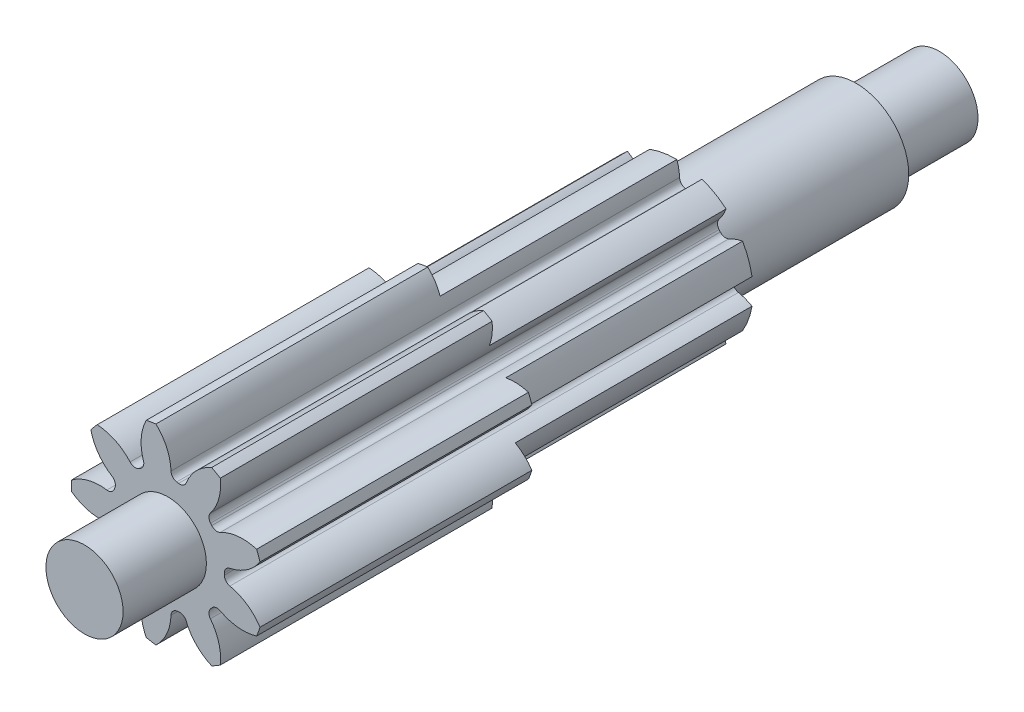
SolidWorks part; units mm, degrees
ref_plane "Front Plane" through (0, 0, 0) normal (0, 0, 1) x (1, 0, 0)
ref_plane "Top Plane" through (0, 0, 0) normal (0, 1, 0) x (1, 0, 0)
ref_plane "Right Plane" through (0, 0, 0) normal (1, 0, 0) x (0, 0, -1)
sketch "Sketch1" plane through (0, 0, 0) normal (0, 0, 1) x (1, 0, 0)
  line L0 (0, 0) -> (0, 0.9) construction
  line L1 (-0.2893, 1.0053) -> (0.2893, 0.7947) construction
  circle A0 centre (0, 0) radius 0.65 construction
  circle A1 centre (0, 0) radius 1.1 construction
  circle A2 centre (0, 0) radius 0.9 construction
  circle A3 centre (0, 0) radius 0.8457 construction
  circle A5 centre (0, 0) radius 0.5 construction
  point P8 (0.1, 0)
  point P13 (4.5, 0)
  dimension "OD" = 2.2
  dimension "Root Diameter" = 1.3
  dimension "Gear Pitch Diameter" = 1.8
  dimension "Base Diameter" = 1.6914
  dimension "For Shaft Diameter" = 1
  dimension "Pressure Angle" = 20
  dimension "Number of Teeth" = 9
  dimension "Module" = 0.2
sketch "Sketch2" plane through (0, 0, 0) normal (1, 0, 0) x (0, 0, -1)
  line L0 (-4.875, 0) -> (4.875, 0) construction
  line L1 (4.875, 1.1) -> (4.875, -1.1) construction
  line L3 (-4.875, 1.1) -> (4.875, 1.1) construction
  line L5 (-4.875, 12.5) -> (-4.875, -12.5) construction
  point P2 (0, 1.1)
  dimension "Overall Width" = 9.75
  dimension "Face Width" = 4.875
sketch "Sketch3" plane through (0, 0, 0) normal (0, 0, 1) x (1, 0, 0)
  circle A0 centre (0, 0) radius 1.1
  circle A1 centre (0, 0) radius 1.1 construction
extrude "Boss-Extrude1" add sketch "Sketch3" against normal up to vertex (4.875 mm away) and the other way up to vertex (4.875 mm away) up to point (0, 0, -4.875) other way up to point (0, 0, 4.875)
sketch "Sketch4" plane through (0, 0, 0) normal (0, 0, 1) x (1, 0, 0)
  line L0 (0.6452, -0.0785) -> (0.6452, 0.0785)
  arc A3 (1.0517, 0.3225) -> (1.0517, -0.3225) centre (0, 0) cw
  circle A4 centre (0, 0) radius 1.1 construction
  arc A5 (1.0517, 0.3225) -> (0.6452, 0.0785) centre (0.5964, 0.6204) cw
  circle A6 centre (0, 0) radius 0.65 construction
  arc A7 (1.0517, -0.3225) -> (0.6452, -0.0785) centre (0.5964, -0.6204) ccw
  spline S0 degree 4 poles (0.835, 0.1344) (0.8354, 0.1345) (0.8366, 0.1347) (0.8388, 0.1353) (0.8424, 0.1363) (0.847, 0.1378) (0.8528, 0.1399) (0.8596, 0.1427) (0.8669, 0.146) (0.8748, 0.1499) (0.8826, 0.1541) (0.8902, 0.1585) (0.8977, 0.1631) (0.9066, 0.1689) (0.9172, 0.1763) (0.9293, 0.1854) (0.9427, 0.1963) (0.9559, 0.208) (0.9686, 0.22) (0.9811, 0.2327) (0.9929, 0.2454) (1.0047, 0.2591) (1.0154, 0.2721) (1.0269, 0.287) (1.0362, 0.2996) (1.05, 0.3198) (1.0557, 0.3287) (1.0642, 0.3422) (1.067, 0.347) knots 0 0 0 0 0 0.005377 0.015084 0.028532 0.04661 0.064855 0.092111 0.119476 0.146842 0.174209 0.201575 0.228941 0.256307 0.307035 0.361767 0.4165 0.471232 0.525964 0.580697 0.635429 0.690161 0.744894 0.799626 0.854358 0.909091 1 1 1 1 1 construction
  spline S1 degree 4 poles (0.835, 0.1344) (0.8354, 0.1345) (0.8366, 0.1347) (0.8388, 0.1353) (0.8424, 0.1363) (0.847, 0.1378) (0.8528, 0.1399) (0.8596, 0.1427) (0.8669, 0.146) (0.8748, 0.1499) (0.8826, 0.1541) (0.8902, 0.1585) (0.8977, 0.1631) (0.9066, 0.1689) (0.9172, 0.1763) (0.9293, 0.1854) (0.9427, 0.1963) (0.9559, 0.208) (0.9686, 0.22) (0.9811, 0.2327) (0.9929, 0.2454) (1.0047, 0.2591) (1.0154, 0.2721) (1.0269, 0.287) (1.0362, 0.2996) (1.0451, 0.3126) (1.0495, 0.3192) (1.0517, 0.3225) knots 0 0 0 0 0 0.005377 0.015084 0.028532 0.04661 0.064855 0.092111 0.119476 0.146842 0.174209 0.201575 0.228941 0.256307 0.307035 0.361767 0.4165 0.471232 0.525964 0.580697 0.635429 0.690161 0.744894 0.799626 0.854358 0.909091 0.909091 0.909091 0.909091 0.909091 construction
  spline S2 degree 4 poles (0.835, -0.1344) (0.8354, -0.1345) (0.8366, -0.1347) (0.8388, -0.1353) (0.8424, -0.1363) (0.847, -0.1378) (0.8528, -0.1399) (0.8596, -0.1427) (0.8669, -0.146) (0.8748, -0.1499) (0.8826, -0.1541) (0.8902, -0.1585) (0.8977, -0.1631) (0.9066, -0.1689) (0.9172, -0.1763) (0.9293, -0.1854) (0.9427, -0.1963) (0.9559, -0.208) (0.9686, -0.22) (0.9811, -0.2327) (0.9929, -0.2454) (1.0047, -0.2591) (1.0154, -0.2721) (1.0269, -0.287) (1.0362, -0.2996) (1.05, -0.3198) (1.0557, -0.3287) (1.0642, -0.3422) (1.067, -0.347) knots 0 0 0 0 0 0.005377 0.015084 0.028532 0.04661 0.064855 0.092111 0.119476 0.146842 0.174209 0.201575 0.228941 0.256307 0.307035 0.361767 0.4165 0.471232 0.525964 0.580697 0.635429 0.690161 0.744894 0.799626 0.854358 0.909091 1 1 1 1 1 construction
  spline S3 degree 4 poles (0.835, -0.1344) (0.8354, -0.1345) (0.8366, -0.1347) (0.8388, -0.1353) (0.8424, -0.1363) (0.847, -0.1378) (0.8528, -0.1399) (0.8596, -0.1427) (0.8669, -0.146) (0.8748, -0.1499) (0.8826, -0.1541) (0.8902, -0.1585) (0.8977, -0.1631) (0.9066, -0.1689) (0.9172, -0.1763) (0.9293, -0.1854) (0.9427, -0.1963) (0.9559, -0.208) (0.9686, -0.22) (0.9811, -0.2327) (0.9929, -0.2454) (1.0047, -0.2591) (1.0154, -0.2721) (1.0269, -0.287) (1.0362, -0.2996) (1.0451, -0.3126) (1.0495, -0.3192) (1.0517, -0.3225) knots 0 0 0 0 0 0.005377 0.015084 0.028532 0.04661 0.064855 0.092111 0.119476 0.146842 0.174209 0.201575 0.228941 0.256307 0.307035 0.361767 0.4165 0.471232 0.525964 0.580697 0.635429 0.690161 0.744894 0.799626 0.854358 0.909091 0.909091 0.909091 0.909091 0.909091 construction
  dimension "D1" = 0.1571
extrude "Cut-Extrude1" cut sketch "Sketch4" against normal through all both and the other way through all
fillet "Fillet1" radius 0.0785 2 edges at (0.6452, -0.0785, 0) (0.6452, 0.0785, 0)
pattern_circular "CirPattern1" count 9 over 360 about axis through (0, 0, 0) along (0, 0, 1) of "Cut-Extrude1", "Fillet1"
sketch "Sketch5" plane through (0, 0, 0) normal (1, 0, 0) x (0, 0, -1)
  line L0 (-5.9186, 0) -> (3.9532, 0) construction
  line L9 (4.875, 0) -> (-4.875, 0) construction
  line L10 (4.875, 1.3) -> (4.875, 0.44)
  line L11 (4.875, 0.44) -> (3.925, 0.44)
  line L12 (3.925, 0.44) -> (3.925, 0.6)
  line L13 (1.875, 0.875) -> (-0.825, 0.875)
  line L14 (-0.825, 0.875) -> (-0.825, 1.3)
  line L15 (-0.825, 1.3) -> (4.875, 1.3)
  line L16 (4.875, -0.0566) -> (4.875, 0.0566) construction
  line L17 (1.875, 0.875) -> (1.875, 0.6)
  line L18 (1.875, 0.6) -> (3.925, 0.6)
  line L19 (-4.875, 0.1651) -> (-4.875, 0.0566) construction
  line L20 (-4.875, 1.3) -> (-3.925, 1.3)
  line L21 (-4.875, 1.3) -> (-4.875, 0.44)
  line L22 (-4.875, 0.44) -> (-3.925, 0.44)
  line L23 (-3.925, 1.3) -> (-3.925, 0.44)
  dimension "D1" = 0.88
  dimension "D2" = 1.75
  dimension "D3" = 2.6
  dimension "D4" = 0.95
  dimension "D5" = 1.2
  dimension "D6" = 2.7
  dimension "D7" = 3
  dimension "D8" = 0.95
revolve "Cut-Revolve1" cut sketch "Sketch5" angle 360 about L0
equation "\"Number of Teeth\"= 9"
equation "\"Module\"= 0.2"
equation "\"Diametral Pitch\"= 1 / \"Module\""
equation "\"Dedendum\"= 1.25 / \"Diametral Pitch\""
equation "\"Pitch Diameter\"= \"Module\" * \"Number of Teeth\""
equation "\"Root Diameter\"= \"Pitch Diameter\" - ( 2 * \"Dedendum\" )"
equation "\"Root Diameter@Sketch1\"=\"Root Diameter\""
equation "\"OD@Sketch1\" = \"Outside Diameter\""
equation "\"D1@CirPattern1\"=\"Number of Teeth\""
equation "\"Pressure Angle\"= 20"
equation "\"Base Diameter\"= \"Pitch Diameter\" * cos ( \"Pressure Angle\" )"
equation "\"Outside Diameter\"= ( \"Number of Teeth\" + 2 ) / \"Diametral Pitch\""
equation "\"Pitch Angle\"= 360deg / \"Number of Teeth\""
equation "\"Alpha\"= sqr ( \"Pitch Diameter\" ^ 2 - \"Base Diameter\" ^ 2 ) / \"Base Diameter\" * 180 / PI - \"Pressure Angle\""
equation "\"Beta\"= ( \"Pitch Angle\" / 4 - \"Alpha\" )"
equation "\"Phi\"= sqr ( ( \"Outside Diameter\" / 2 ) ^ 2 - ( \"Base Diameter\" / 2 ) ^ 2 ) / ( \"Base Diameter\" / 2 )"
equation "\"Addendum\"= 1 / \"Diametral Pitch\""
equation "\"WorkingDepth\"= 2 / \"Diametral Pitch\""
equation "\"WholeDepth\"= 2.25 / \"Diametral Pitch\""
equation "\"Clearance\"= 0.25 / \"Diametral Pitch\""
equation "\"ToothThickness\"= ( pi * 2 ) / \"Diametral Pitch\""
equation "\"CircularPitch\"= pi / \"Diametral Pitch\""
equation "\"Number of Teeth@Sketch1\"=\"Number of Teeth\""
equation "\"Module@Sketch1\"=\"Module\""
equation "\"Pressure Angle@Sketch1\"=\"Pressure Angle\""
equation "\"Gear Pitch Diameter@Sketch1\"=\"Pitch Diameter\""
equation "\"Base Diameter@Sketch1\"=\"Base Diameter\""
equation "\"Fillet\"= \"Clearance\" * cos ( \"Pressure Angle\" ) * tan ( ( 90 + \"Pressure Angle\" ) / 2 )"
equation "\"D1\"= \"Fillet\""
equation "\"D1\"= \"Set Screw Pitch@Sketch1\" * .75"
equation "\"D1\"= \"Set Screw Diameter@Sketch1\" / 2"
equation "\"D3\"= \"Set Screw Pitch@Sketch1\" +  ( \"Hub Diameter@Sketch1\" / 2 ) "
equation "\"D4\"= \"Set Screw Pitch@Sketch1\""
equation "\"D2\"= \"Fillet\" * 2"
equation "\"D1\"= \"Fillet\" * 2"
equation "\"D1\" = \"Fillet\""
equation "\"D1@Sketch4\"=\"CircularPitch\"*0.25"
equation "\"D1@Fillet1\"=\"CircularPitch\"*0.125"
